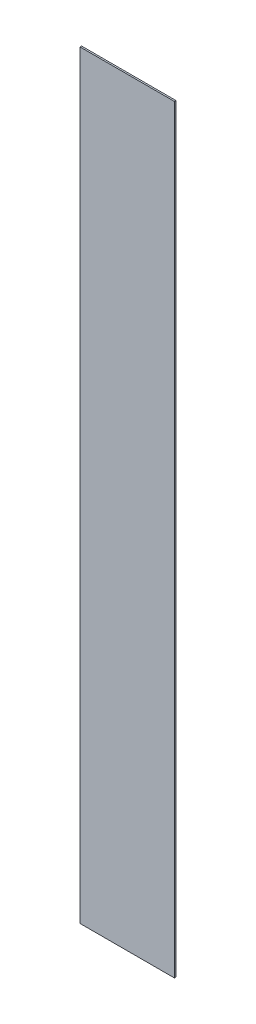
SolidWorks part; units mm, degrees
ref_plane "Front Plane" through (0, 0, 0) normal (0, 0, 1) x (1, 0, 0)
ref_plane "Top Plane" through (0, 0, 0) normal (0, 1, 0) x (1, 0, 0)
ref_plane "Right Plane" through (0, 0, 0) normal (1, 0, 0) x (0, 0, -1)
sketch "Sketch1" plane through (0, 0, 0) normal (0, 0, 1) x (1, 0, 0)
  line L1 (300, -2411.5) -> (-300, -2411.5)
  line L2 (300, -2411.5) -> (300, 2411.5)
  line L3 (300, 2411.5) -> (-300, 2411.5)
  line L4 (-300, -2411.5) -> (-300, 2411.5)
  line L5 (300, -2411.5) -> (-300, 2411.5) construction
  line L6 (300, 2411.5) -> (-300, -2411.5) construction
  point P0 (0, 0)
extrude "Boss-Extrude1" add sketch "Sketch1" along normal blind 10
